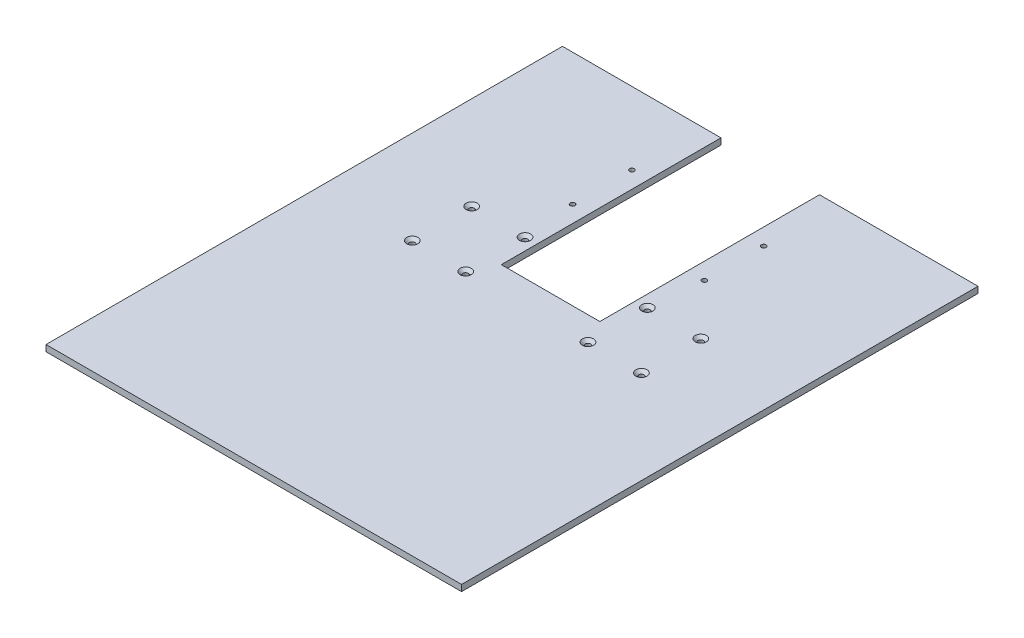
SolidWorks part; units mm, degrees
ref_plane "Front Plane" through (0, 0, 0) normal (0, 0, 1) x (1, 0, 0)
ref_plane "Top Plane" through (0, 0, 0) normal (0, 1, 0) x (1, 0, 0)
ref_plane "Right Plane" through (0, 0, 0) normal (1, 0, 0) x (0, 0, -1)
sketch "Sketch1" plane through (0, 0, 0) normal (0, 1, 0) x (1, 0, 0)
  line L1 (-260.3306, -327.4793) -> (89.6694, -327.4793)
  line L2 (-260.3306, -327.4793) -> (-260.3306, -77.4793)
  line L3 (-260.3306, -77.4793) -> (89.6694, -77.4793)
  line L4 (89.6694, -327.4793) -> (89.6694, -77.4793)
  dimension "D1" = 250
  dimension "D2" = 350
extrude "Boss-Extrude1" add sketch "Sketch1" along normal blind 5.3
ref_plane "Plane1" through (0, 0, 202.4793) normal (0, 0, -1) x (-1, 0, 0)
sketch "Sketch4" plane through (0, 0, 77.4793) normal (0, 0, -1) x (-1, 0, 0)
  line L0 (-89.6694, 5.3) -> (260.3306, 5.3) construction
  line L2 (126.8306, 5.3) -> (260.3306, 5.3)
  line L3 (126.8306, 5.3) -> (126.8306, 0)
  line L4 (126.8306, 0) -> (260.3306, 0)
  line L5 (260.3306, 5.3) -> (260.3306, 0)
  line L6 (43.8306, 5.3) -> (-89.6694, 5.3)
  line L7 (43.8306, 5.3) -> (43.8306, 0)
  line L8 (43.8306, 0) -> (-89.6694, 0)
  line L9 (-89.6694, 5.3) -> (-89.6694, 0)
  point P0 (85.3306, 5.3)
  dimension "D1" = 41.5
  dimension "D2" = 41.5
extrude "Boss-Extrude3" add sketch "Sketch4" along normal blind 185
ref_plane "Plane2" through (0, 0, -15.0207) normal (0, 0, -1) x (-1, 0, 0)
sketch "Sketch5" plane through (0, 5.3, 0) normal (0, 1, 0) x (1, 0, 0)
  line L0 (-33.8306, 107.5207) -> (-33.8306, -47.4793)
  line L1 (-43.8306, 107.5207) -> (89.6694, 107.5207) construction
  line L2 (-33.8306, -47.4793) -> (-33.8306, -97.4793)
  line L3 (-43.8306, 107.5207) -> (-43.8306, -77.4793) construction
  line L4 (-136.8306, 107.5207) -> (-136.8306, -97.4793)
  line L5 (-260.3306, 107.5207) -> (-126.8306, 107.5207) construction
  line L6 (-136.8306, -97.4793) -> (-136.8306, -47.4793)
  line L7 (-126.8306, 107.5207) -> (-126.8306, -77.4793) construction
  line L8 (-29.8306, 107.5207) -> (-29.8306, 46.5207)
  line L9 (-29.8306, 46.5207) -> (-29.8306, -3.4793)
  line L10 (-140.8306, 107.5207) -> (-140.8306, 46.5207)
  line L11 (-140.8306, 46.5207) -> (-140.8306, -3.4793)
  line L12 (-136.8306, -97.4793) -> (-181.8306, -97.4793)
  line L13 (-136.8306, -47.4793) -> (-181.8306, -47.4793)
  line L14 (-33.8306, -97.4793) -> (11.1694, -97.4793)
  line L15 (-33.8306, -47.4793) -> (11.1694, -47.4793)
  dimension "D1" = 10
  dimension "D2" = 10
  dimension "D3" = 155
  dimension "D4" = 50
  dimension "D5" = 50
  dimension "D6" = 155
  dimension "D7" = 14
  dimension "D8" = 14
  dimension "D9" = 61
  dimension "D10" = 50
  dimension "D11" = 61
  dimension "D12" = 50
  dimension "D13" = 45
  dimension "D14" = 45
  dimension "D15" = 45
  dimension "D16" = 45
hole_wizard "Ø4.0mm Dowel Hole1" positions "Sketch8" profile "Sketch9" hole size "Ø4.0" standard "ANSI Metric" end condition through all
sketch "Sketch8" plane through (0, 5.3, 0) normal (0, 1, 0) x (1, 0, 0)
  point P0 (-181.8306, -47.4793)
  point P3 (-181.8306, -97.4793)
  point P6 (-136.8306, -97.4793)
  point P9 (-136.8306, -47.4793)
  point P12 (-33.8306, -47.4793)
  point P15 (11.1694, -47.4793)
  point P18 (11.1694, -97.4793)
  point P21 (-33.8306, -97.4793)
  point P24 (-29.8306, -3.4793)
  point P27 (-29.8306, 46.5207)
  point P30 (-140.8306, 46.5207)
  point P33 (-140.8306, -3.4793)
sketch "Sketch9" plane through (-181.8306, 5.3, 47.4793) normal (1, 0, 0) x (0, 0, 1)
  line L0 (0, 0) -> (0, 5.3)
  line L1 (0, 5.3) -> (2, 5.3)
  line L2 (2, 5.3) -> (2, 0)
  line L5 (2, 0) -> (0, 0)
  line L11 (0, -6.35) -> (0, 107.95) construction
  dimension "Thru Hole Dia." = 4
  dimension "Thru Hole Depth" = 5.3
hole_wizard "CSK for M4 Flat Head Machine Screw2" positions "Sketch10" profile "Sketch11" countersink size "M4" standard "ANSI Metric" end condition through all
sketch "Sketch10" plane through (0, 5.3, 0) normal (0, 1, 0) x (1, 0, 0)
  point P0 (-181.8306, -47.4793)
  point P3 (-136.8306, -47.4793)
  point P6 (-181.8306, -97.4793)
  point P9 (-136.8306, -97.4793)
  point P12 (-33.8306, -47.4793)
  point P15 (11.1694, -47.4793)
  point P18 (11.1694, -97.4793)
  point P21 (-33.8306, -97.4793)
sketch "Sketch11" plane through (-181.8306, 5.3, 47.4793) normal (1, 0, 0) x (0, 0, 1)
  line L0 (0, 0) -> (0, 5.3)
  line L1 (0, 5.3) -> (2.25, 5.3)
  line L2 (2.25, 5.3) -> (2.25, 2.45)
  line L3 (2.25, 2.45) -> (4.7, 0)
  line L5 (4.7, 0) -> (0, 0)
  line L6 (-2.25, 2.45) -> (-4.7, 0) construction
  line L11 (0, -6.35) -> (0, 107.95) construction
  dimension "Thru Hole Dia." = 4.5
  dimension "Thru Hole Depth" = 5.3
  dimension "Near C'Sink Dia." = 9.4
  dimension "Near C'Sink Angle" = 90
